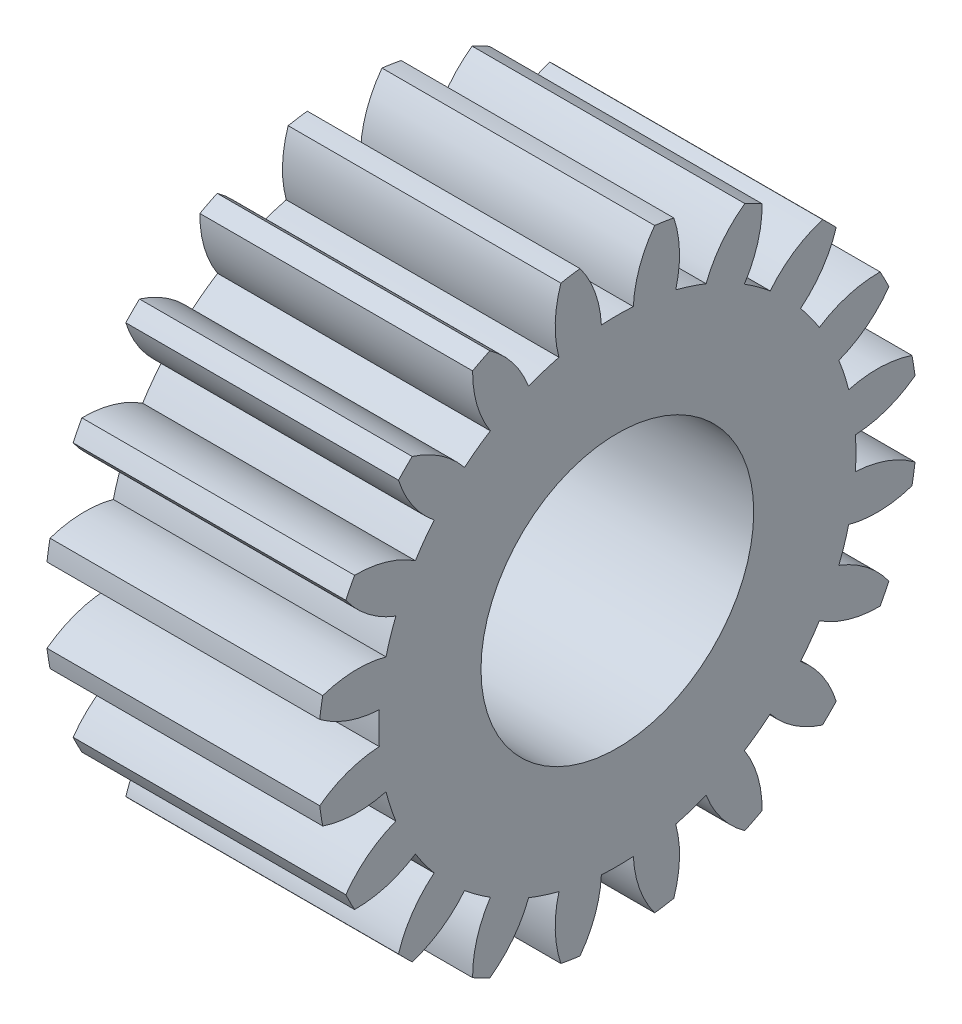
SolidWorks part; units mm, degrees
ref_plane "Plane1" through (0, 0, 0) normal (0, 0, 1) x (1, 0, 0)
ref_plane "Plane2" through (0, 0, 0) normal (0, 1, 0) x (1, 0, 0)
ref_plane "Plane3" through (0, 0, 0) normal (1, 0, 0) x (0, 0, -1)
sketch "HoldingSke" plane through (0, 0, 0) normal (0, 1, 0) x (1, 0, 0)
  line L0 (0, 0) -> (0.6265, -0.228)
  line L1 (-15, 0) -> (100, 0) construction
  line L2 (0, 0) -> (-2.1039, 2.3779)
  line L3 (0, 0) -> (-11.863, 4.5341)
  line L4 (0, 0) -> (8.1152, 2.9537)
  line L5 (0, 0) -> (-46.8476, -17.4728)
  line L6 (0, 0) -> (-12.4344, -8.3896)
  line L7 (-2.1039, 2.3779) -> (8.6586, 51.2059)
  line L8 (-76.2, 54.61) -> (-73.9, 54.61)
  line L9 (-67.7845, 28.3722) -> (-49.3413, 33.142)
  line L10 (-76.2, 71.12) -> (104.1128, 71.12)
  line L11 (0, 0) -> (-15, 0)
  line L12 (-76.2, 101.6) -> (-76.147, 101.6)
  line L13 (24.9733, 27.94) -> (52.9518, 28.4284)
  line L14 (24.9733, 27.94) -> (24.9743, 27.94)
  line L15 (24.9733, 27.94) -> (100.4006, 29.5858)
  line L16 (-63.627, -1.5) -> (-12.827, -1.5)
  circle A0 centre (0, 0) radius 7.5
  circle A1 centre (0, 0) radius 13.124
  circle A2 centre (0, 0) radius 37.5
  circle A3 centre (0, 0) radius 7.5
  dimension "MHD" = 26.248
  dimension "Hub_dia" = 75
  dimension "Bore" = 15
  dimension "MBD" = 15
  dimension "Num_teeth" = 20
  dimension "Pitch" = 0.6667
  dimension "Overall_len" = 50
  dimension "Show_teeth" = 20
  dimension "Thickness" = 15
  dimension "OAL" = 50.0001
  dimension "T_dim" = 2.3
  dimension "Ap" = 14.5
  dimension "H" = 19.05
  dimension "Pitch_radius" = 180.3128
  dimension "Width" = 15
  dimension "Backlash" = 0.053
  dimension "Addendum_fac" = 1
  dimension "Dedendum_fac" = 1.25
  dimension "Clearance_fac" = 0.25
  dimension "Dedendum_add" = 0.001
  dimension "Module" = 1.5
sketch "BasProSke" plane through (0, 0, 0) normal (0, 1, 0) x (1, 0, 0)
  line L0 (-10, 0) -> (60, 0) construction
  line L1 (0, 0) -> (0, 16.5)
  line L2 (0, 0) -> (15, 0)
  line L3 (15, 0) -> (15, 16.5)
  line L4 (15, 16.5) -> (0, 16.5)
  dimension "Thickness" = 15
  dimension "Diameter" = 33
revolve "Base-Revolve" add sketch "BasProSke" angle 360 about L0
sketch "TooCutSke" plane through (0, 0, 0) normal (1, 0, 0) x (0, 0, -1)
  line L1 (0, 0) -> (0, 107) construction
  line L2 (0, 0) -> (-1.2696, 14.9462) construction
  line L3 (0, 0) -> (-4.6808, 29.5532) construction
  line L4 (-1.2696, 14.9462) -> (-2.3404, 14.7766) construction
  arc A0 (0.8779, 13.0946) -> (-0.8779, 13.0946) centre (0, 0) ccw
  arc A1 (2.0711, 16.3951) -> (-2.0711, 16.3951) centre (0, 0) ccw
  circle A2 centre (0, 0) radius 15 construction
  circle A3 centre (0, 0) radius 14.5222 construction
  arc A4 (-0.8779, 13.0946) -> (-2.0711, 16.3951) centre (-6.8704, 12.7942) ccw
  arc A5 (2.0711, 16.3951) -> (0.8779, 13.0946) centre (6.8704, 12.7942) ccw
  dimension "Root_dia" = 26.248
  dimension "Overcut_dia" = 33.0508
  dimension "Pitch_dia" = 30
  dimension "Base_dia" = 29.0444
  dimension "Flank_rad" = 6
  dimension "Half_ang" = 9
  dimension "Half_CT" = 1.0841
extrude "ToothCut" cut sketch "TooCutSke" along normal through all
fillet "Breaks" [suppressed] radius 0.03
fillet "RootFillets" [suppressed] radius 0.376
pattern_circular "TeethCuts" count 20 every 18 about axis through (-10, 0, 0) along (1, 0, 0) of "ToothCut", "RootFillets", "Breaks"
sketch "HubNeaOneSke" plane through (0, 0, 0) normal (-1, 0, 0) x (0, 0, 1)
  circle A0 centre (0, 0) radius 13.124
  dimension "Diameter" = 26.248
extrude "HubNearOne" [suppressed] add sketch "HubNeaOneSke" along normal blind 35.0001
sketch "HubNeaBotSke" plane through (0, 0, 0) normal (-1, 0, 0) x (0, 0, 1)
  circle A0 centre (0, 0) radius 13.124
  dimension "Diameter" = 26.248
extrude "HubNearBoth" [suppressed] add sketch "HubNeaBotSke" along normal blind 17.5
ref_plane "FarPln" through (15, 0, 0) normal (1, 0, 0) x (0, 0, -1)
sketch "HubFarSke" plane through (15, 0, 0) normal (1, 0, 0) x (0, 0, -1)
  circle A0 centre (0, 0) radius 13.124
  dimension "Diameter" = 26.248
extrude "HubFar" [suppressed] add sketch "HubFarSke" along normal blind 17.5
sketch "BorSke" plane through (0, 0, 0) normal (1, 0, 0) x (0, 0, -1)
  circle A0 centre (0, 0) radius 7.5
  dimension "Diameter" = 15
extrude "Bore" cut sketch "BorSke" along normal mid plane 100.0001
sketch "KeySke" plane through (0, 0, 0) normal (1, 0, 0) x (0, 0, -1)
  line L0 (-2.5, 0) -> (-2.5, 9.8)
  line L1 (-2.5, 9.8) -> (2.5, 9.8)
  line L2 (2.5, 9.8) -> (2.5, 0)
  line L3 (0, 0) -> (0, 34) construction
  line L4 (-2.5, 0) -> (2.5, 0)
  dimension "Offset" = 9.8
  dimension "Width" = 5
extrude "Keyway" [suppressed] cut sketch "KeySke" along normal mid plane 100.0001
pattern_circular "Keyway2" [suppressed] count 2 every 90 about axis through (-10, 0, 0) along (1, 0, 0)
equation "' \"Module@HoldingSke\" = 6.35"
equation "' \"Num_teeth@HoldingSke\" = 12"
equation "' \"Ap@HoldingSke\" =  20"
equation "' \"Ap@HoldingSke\" = 20"
equation "' \"Width@HoldingSke\" = 0.5 * 25.4"
equation "' \"Hub_dia@HoldingSke\"= 1 * 25.4"
equation "' \"Hub_dia@HoldingSke\" = 1 * 25.4"
equation "' \"Overall_len@HoldingSke\" = 1.0 * 25.4"
equation "' \"Bore@HoldingSke\" = 0.75 * 25.4"
equation "' \"T_dim@HoldingSke\" = 0.1 * 25.4"
equation "' \"Width@KeySke\" = 0.25 * 25.4"
equation "' \"Show_teeth@HoldingSke\" = 13"
equation "' \"Backlash@HoldingSke\" = 0.009 * 25.4"
equation "' \"Addendum_fac@HoldingSke\" = 1.0"
equation "' \"Dedendum_fac@HoldingSke\" = 1.25"
equation "' \"Dedendum_add@HoldingSke\" = 0.00005 * 25.4"
equation "' \"Clearance_fac@HoldingSke\" = 0.25"
equation "\"Pitch@HoldingSke\" = 1 / \"Module@HoldingSke\""
equation "\"Overcut_dia@TooCutSke\" = (\"Num_teeth@HoldingSke\" + 2 * \"Addendum_fac@HoldingSke\") / \"Pitch@HoldingSke\" + 0.002 * 25.4"
equation "\"Pitch_dia@TooCutSke\" = \"Num_teeth@HoldingSke\" / \"Pitch@HoldingSke\""
equation "\"Base_dia@TooCutSke\" = \"Num_teeth@HoldingSke\" / \"Pitch@HoldingSke\" * cos((\"Ap@HoldingSke\"  * 3.14159265 / 180))"
equation "\"Root_dia@TooCutSke\" = (\"Num_teeth@HoldingSke\" + 2) / \"Pitch@HoldingSke\" - 2 * (\"Addendum_fac@HoldingSke\" + \"Dedendum_fac@HoldingSke\") / \"Pitch@HoldingSke\" - \"Dedendum_add@HoldingSke\" * 2"
equation "\"Half_ang@TooCutSke\" = 180 / \"Num_teeth@HoldingSke\""
equation "\"Half_CT@TooCutSke\" = \"Num_teeth@HoldingSke\" / \"Pitch@HoldingSke\" * sin((3.14159265 / 2 / \"Num_teeth@HoldingSke\")) / 2 - 7 * \"Backlash@HoldingSke\" / 4"
equation "\"Flank_rad@TooCutSke\" = \"Num_teeth@HoldingSke\" / \"Pitch@HoldingSke\" / 5"
equation "\"Radius@RootFillets\" = \"Clearance_fac@HoldingSke\" / \"Pitch@HoldingSke\" + \"Dedendum_add@HoldingSke\""
equation "\"Break_rad@Breaks\" = 0.02 / \"Pitch@HoldingSke\""
equation "\"Thickness@HoldingSke\" = \"Width@HoldingSke\""
equation "\"OAL@HoldingSke\" = \"Thickness@HoldingSke\""
equation "\"MHD@HoldingSke\" = (\"Num_teeth@HoldingSke\" + 2) / \"Pitch@HoldingSke\" - 2 * (\"Addendum_fac@HoldingSke\" + \"Dedendum_fac@HoldingSke\")  / \"Pitch@HoldingSke\" - \"Dedendum_add@HoldingSke\" * 2"
equation "\"MBD@HoldingSke\" = (\"Num_teeth@HoldingSke\" + 2) / \"Pitch@HoldingSke\" - 2 * (\"Addendum_fac@HoldingSke\" + \"Dedendum_fac@HoldingSke\")  / \"Pitch@HoldingSke\" - \"Dedendum_add@HoldingSke\" * 2 - 0.002 * 25.4"
equation "\"MHD@HoldingSke\" = ((sgn( \"MHD@HoldingSke\" - \"Hub_dia@HoldingSke\" )-1)*( \"MHD@HoldingSke\" - \"Hub_dia@HoldingSke\" ))/-2+ \"Hub_dia@HoldingSke\""
equation "\"MBD@HoldingSke\" = ((sgn( \"MBD@HoldingSke\" - \"Bore@HoldingSke\" )-1)*( \"MBD@HoldingSke\" - \"Bore@HoldingSke\" ))/-2+ \"Bore@HoldingSke\""
equation "\"OAL@HoldingSke\" = ((sgn( \"OAL@HoldingSke\" - \"Overall_len@HoldingSke\" )+1)*( \"OAL@HoldingSke\" - \"Overall_len@HoldingSke\" ))/2 + \"Overall_len@HoldingSke\" + 0.000002 * 25.4"
equation "\"Num_teeth@TeethCuts\" = int( \"Show_teeth@HoldingSke\" ) + 1"
equation "\"Num_teeth@TeethCuts\" = ((sgn( \"Num_teeth@TeethCuts\" - \"Num_teeth@HoldingSke\" )-1)*( \"Num_teeth@TeethCuts\" - \"Num_teeth@HoldingSke\" ))/-2+ \"Num_teeth@HoldingSke\""
equation "\"Num_teeth@TeethCuts\" = ((sgn( \"Num_teeth@TeethCuts\" - 2.0)+1)*( \"Num_teeth@TeethCuts\" - 2.0))/2 +2.0"
equation "\"Angle@TeethCuts\" = 360.0 / \"Num_teeth@HoldingSke\""
equation "\"Diameter@BasProSke\" = (\"Num_teeth@HoldingSke\" + 2 * \"Addendum_fac@HoldingSke\") / \"Pitch@HoldingSke\""
equation "\"Thickness@BasProSke\"  = \"Thickness@HoldingSke\""
equation "' \"Fillet_rad@BasProSke\" =  \"Thickness@HoldingSke\" * 0.05"
equation "' \"Fillet_rad@BasProSke\" = \"Thickness@HoldingSke\" * 0.05"
equation "\"MHD@HoldingSke\" = ((sgn( \"MHD@HoldingSke\" - \"Root_dia@TooCutSke\" )-1)*( \"MHD@HoldingSke\" - \"Root_dia@TooCutSke\" ))/-2+ \"Root_dia@TooCutSke\""
equation "\"Diameter@HubNeaOneSke\" = \"MHD@HoldingSke\""
equation "\"Length@HubNearOne\" = \"OAL@HoldingSke\" - \"Thickness@BasProSke\""
equation "\"Diameter@HubNeaBotSke\" = \"MHD@HoldingSke\""
equation "\"Length@HubNearBoth\" = ( \"OAL@HoldingSke\" - \"Thickness@BasProSke\" ) / 2.0"
equation "\"Thickness@FarPln\" = \"Thickness@BasProSke\""
equation "\"Diameter@HubFarSke\" = \"MHD@HoldingSke\""
equation "\"Length@HubFar\" = ( \"OAL@HoldingSke\" - \"Thickness@BasProSke\" ) / 2.0"
equation "\"Diameter@BorSke\" = \"MBD@HoldingSke\""
equation "\"D1@Bore\" = \"OAL@HoldingSke\" * 2.0"
equation "\"D1@Keyway\" = \"OAL@HoldingSke\" * 2.0"
equation "\"Offset@KeySke\" = \"T_dim@HoldingSke\" + \"MBD@HoldingSke\" / 2.0"
